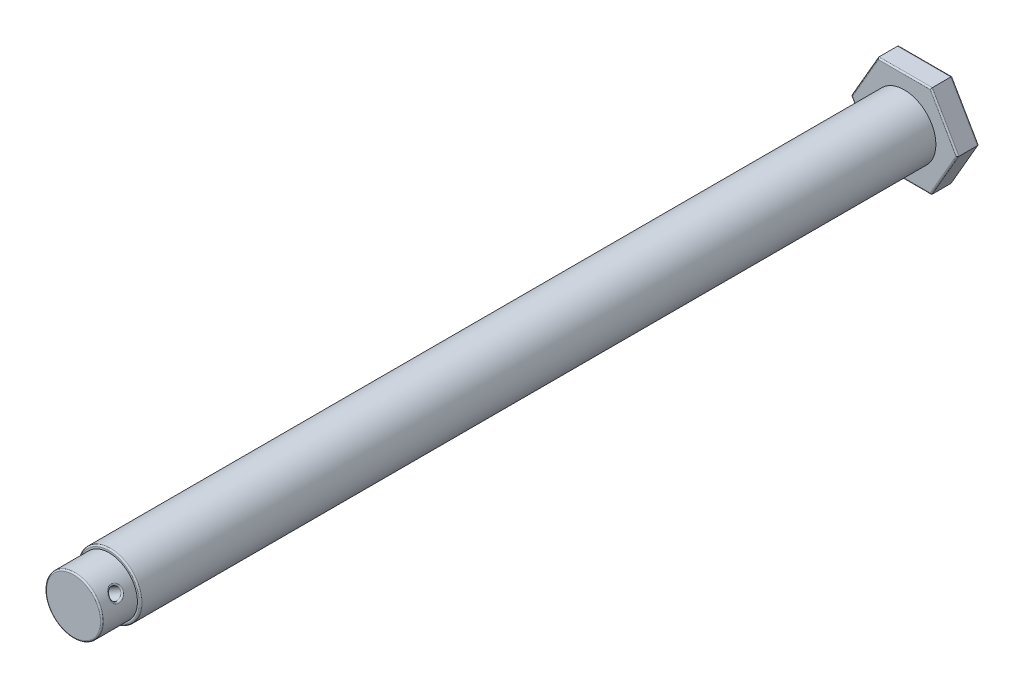
SolidWorks part; units mm, degrees
ref_plane "前视基准面" through (0, 0, 0) normal (0, 0, 1) x (1, 0, 0)
ref_plane "上视基准面" through (0, 0, 0) normal (0, 1, 0) x (1, 0, 0)
ref_plane "右视基准面" through (0, 0, 0) normal (1, 0, 0) x (0, 0, -1)
sketch "草图1" plane through (0, 0, 0) normal (0, 0, 1) x (1, 0, 0)
  line L0 (41.2805, 0) -> (-41.2805, 0) construction
  line L1 (37.5278, 0) -> (18.7639, 32.5)
  line L2 (18.7639, 32.5) -> (-18.7639, 32.5)
  line L3 (-18.7639, 32.5) -> (-37.5278, 0)
  line L4 (-37.5278, 0) -> (-18.7639, -32.5)
  line L5 (-18.7639, -32.5) -> (18.7639, -32.5)
  line L6 (18.7639, -32.5) -> (37.5278, 0)
  circle A0 centre (0, 0) radius 32.5 construction
  dimension "D1" = 65
extrude "拉伸1" add sketch "草图1" along normal blind 15
sketch "草图2" plane through (0, 0, 15) normal (0, 0, 1) x (1, 0, 0)
  circle A0 centre (0, 0) radius 22.25
  dimension "D1" = 44.5
extrude "拉伸2" add sketch "草图2" along normal blind 560
sketch "草图3" plane through (0, 0, 575) normal (0, 0, 1) x (1, 0, 0)
  circle A0 centre (0, 0) radius 20
  dimension "D1" = 40
extrude "拉伸3" add sketch "草图3" along normal blind 25
sketch "草图4" plane through (-28.1458, -16.25, 0) normal (-0.866, -0.5, 0) x (0, 0, 1)
  line L0 (0, 0) -> (600, 0) construction
  line L1 (600, -20) -> (600, 20) construction
  circle A0 centre (587.5, 0) radius 4
  dimension "D2" = 8
  dimension "D1" = 12.5
extrude "拉伸4" cut sketch "草图4" against normal through all
fillet "圆角1" radius 1 16 edges at (28.1458, 16.25, 0) (0, 32.5, 0) (-28.1458, 16.25, 0) (-28.1458, -16.25, 0) (0, -32.5, 0) (28.1458, -16.25, 0) (15.0295, 13.1952, 586.6685) (-18.9421, -6.4183, 588.3315) (-28.1458, -16.25, 15) (0, -32.5, 15) (28.1458, -16.25, 15) (28.1458, 16.25, 15) (-28.1458, 16.25, 15) (0, 32.5, 15) (22.25, 0, 575) (20, 0, 600)
